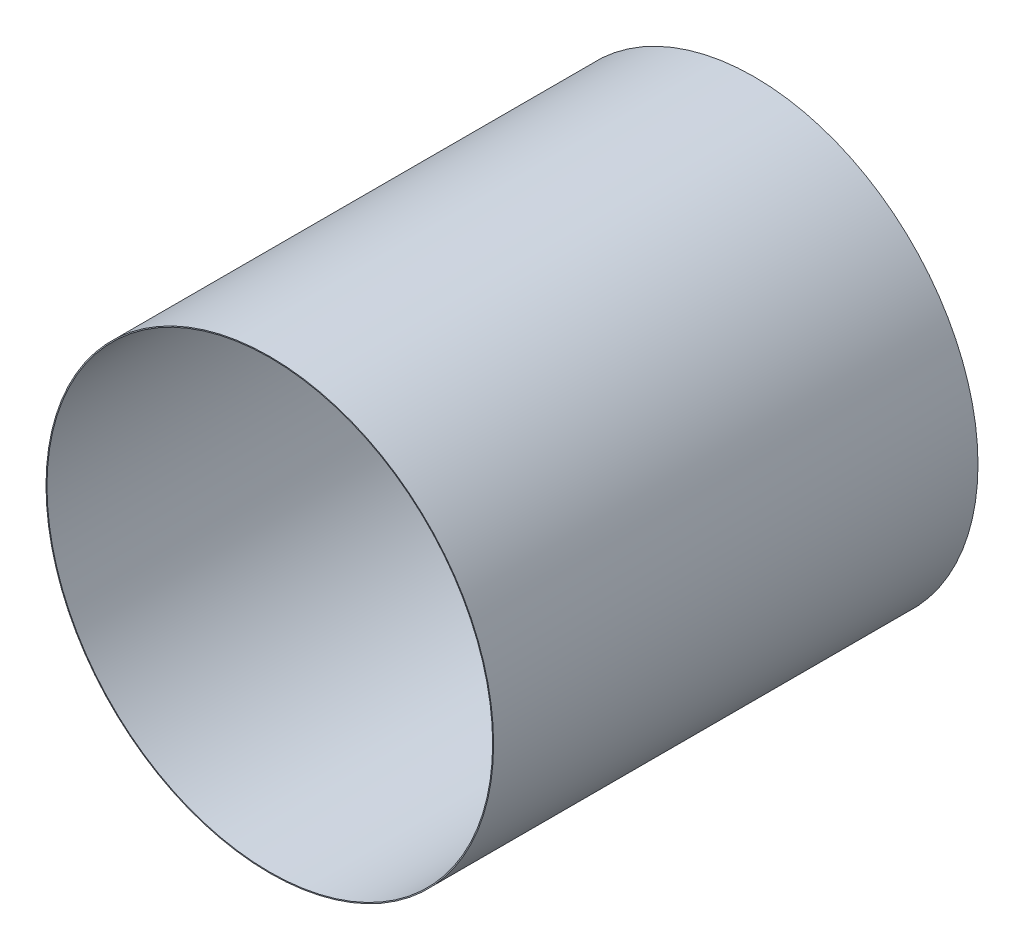
SolidWorks part; units mm, degrees
ref_plane "Front Plane" through (0, 0, 0) normal (0, 0, 1) x (1, 0, 0)
ref_plane "Top Plane" through (0, 0, 0) normal (0, 1, 0) x (1, 0, 0)
ref_plane "Right Plane" through (0, 0, 0) normal (1, 0, 0) x (0, 0, -1)
sketch "Sketch1" plane through (0, 0, 0) normal (0, 0, 1) x (1, 0, 0)
  circle A0 centre (0, 0) radius 11.55
  circle A1 centre (0, 0) radius 11.5
  dimension "D1" = 23
  dimension "D2" = 23.1
extrude "Boss-Extrude1" add sketch "Sketch1" along normal blind 25
